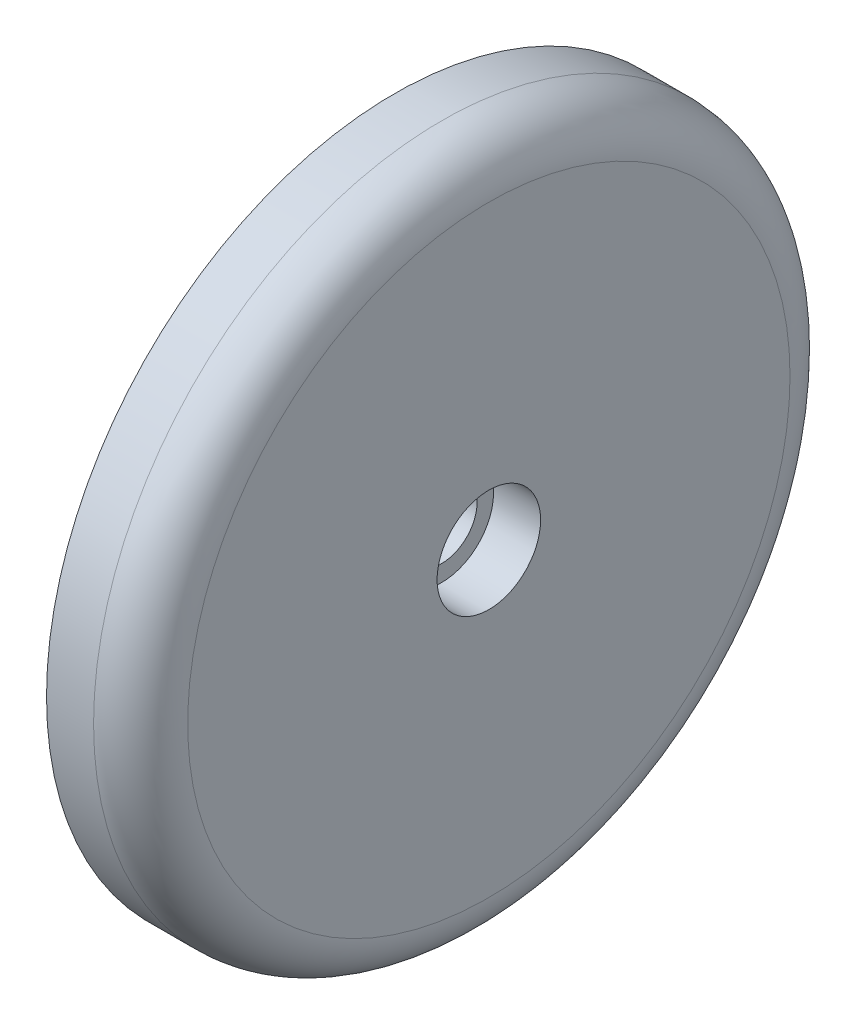
SolidWorks part; units mm, degrees
ref_plane "Plan de face" through (0, 0, 0) normal (0, 0, 1) x (1, 0, 0)
ref_plane "Plan de dessus" through (0, 0, 0) normal (0, 1, 0) x (1, 0, 0)
ref_plane "Plan de droite" through (0, 0, 0) normal (1, 0, 0) x (0, 0, -1)
sketch "Esquisse1" plane through (0, 0, 0) normal (0, 0, 1) x (1, 0, 0)
  line L0 (-20.7863, 2.2) -> (-22.7863, 2.2)
  line L1 (-22.7863, 2.2) -> (-22.7863, 1.5)
  line L2 (-22.7863, 1.5) -> (-27.7863, 1.5)
  line L3 (-20.7863, 2.2) -> (-20.7863, 14.8)
  line L4 (-20.7863, 14.8) -> (-24.7863, 14.8)
  line L5 (-24.7863, 14.8) -> (-24.7863, 13)
  line L6 (-24.7863, 13) -> (-25.7863, 13)
  line L7 (-25.7863, 13) -> (-25.7863, 12)
  line L8 (-25.7863, 12) -> (-21.7863, 12)
  line L9 (-21.7863, 12) -> (-21.7863, 4)
  line L10 (0, 0) -> (-15.3471, 0) construction
  line L11 (-27.7863, 1.5) -> (-27.7863, 4)
  line L12 (-27.7863, 4) -> (-21.7863, 4)
  dimension "D1" = 14.8
  dimension "D2" = 13
  dimension "D3" = 1
  dimension "D4" = 4
  dimension "D5" = 4
  dimension "D6" = 1
  dimension "D7" = 1.5
  dimension "D8" = 2.2
  dimension "D9" = 2
  dimension "D10" = 5
  dimension "D11" = 4
revolve "Révolution1" add sketch "Esquisse1" angle 360 about L10
sketch "Esquisse2" plane through (-25.7863, 0, 0) normal (-1, 0, 0) x (0, 0, 1)
  line L0 (-21.4369, 0) -> (27.5948, 0) construction
  line L1 (20.2232, 4) -> (-22.1689, 4) construction
  line L2 (-19.3124, -4) -> (20.2232, -4) construction
  line L3 (-12.3693, 4) -> (-9.4182, 4)
  line L4 (-9.4182, 4) -> (-9.4182, -4)
  line L5 (-9.4182, -4) -> (-12.3693, -4)
  line L6 (0, -8.1348) -> (0, 4.9057) construction
  line L7 (9.4182, 4) -> (9.4182, -4)
  line L8 (12.3693, 4) -> (9.4182, 4)
  line L9 (9.4182, -4) -> (12.3693, -4)
  arc A0 (-12.3693, 4) -> (-12.3693, -4) centre (0, 0) ccw
  arc A1 (12.3693, 4) -> (12.3693, -4) centre (0, 0) cw
  dimension "D1" = 4
  dimension "D2" = 4
extrude "Enlèv. mat.-Extru.6" cut sketch "Esquisse2" against normal blind 4
fillet "Congé3" radius 1 8 edges at (-21.7863, -4, -11.8415) (-21.7863, 0, -13) (-21.7863, 4, -11.8415) (-21.7863, 12, 0) (-21.7863, 4, 11.8415) (-21.7863, 0, 13) (-21.7863, -4, 11.8415) (-21.7863, -12, 0)
fillet "Congé2" radius 2 1 edges at (-20.7863, 0, -14.8)
sketch "Esquisse3" plane through (-21.7863, 0, 0) normal (-1, 0, 0) x (0, 0, 1)
  circle A0 centre (0, 0) radius 6.1962 construction
  text T0 "www.a4.fr" font "Arial Narrow" height 4
extrude "Boss.-Extru.1" add sketch "Esquisse3" along normal blind 0.5
